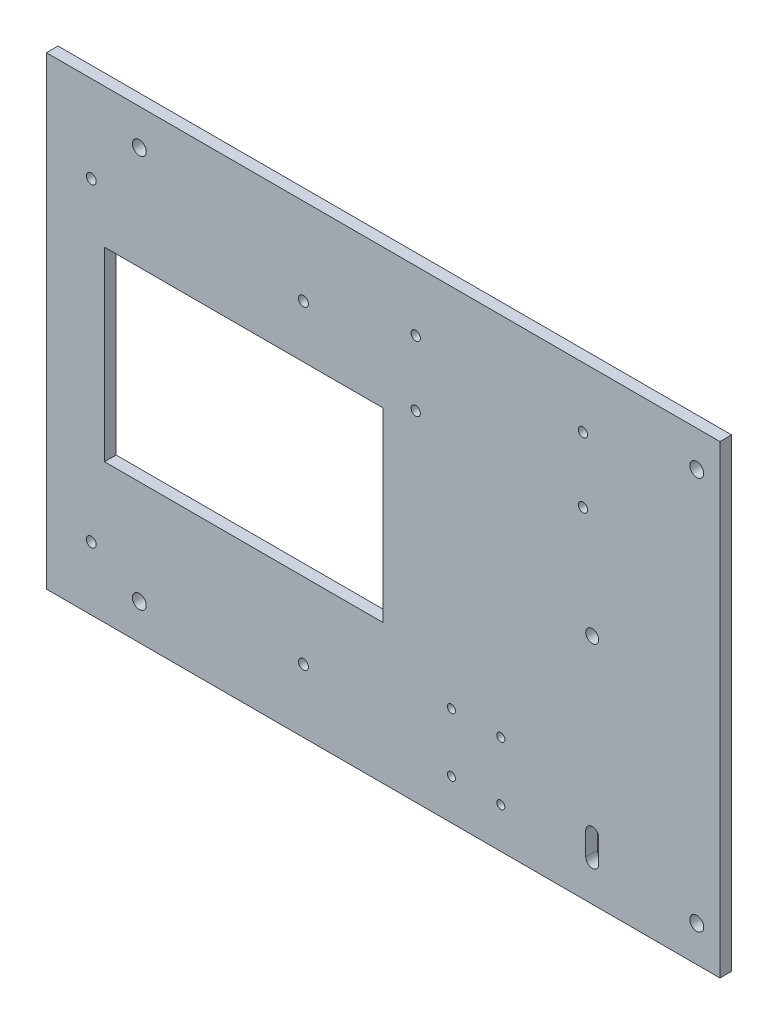
SolidWorks part; units mm, degrees
ref_plane "Front Plane" through (0, 0, 0) normal (0, 0, 1) x (1, 0, 0)
ref_plane "Top Plane" through (0, 0, 0) normal (0, 1, 0) x (1, 0, 0)
ref_plane "Right Plane" through (0, 0, 0) normal (1, 0, 0) x (0, 0, -1)
sketch "Sketch1" plane through (0, 0, 0) normal (0, 0, 1) x (1, 0, 0)
  line L1 (-92.075, 63.5) -> (92.075, 63.5)
  line L2 (-92.075, 63.5) -> (-92.075, -63.5)
  line L3 (-92.075, -63.5) -> (92.075, -63.5)
  line L4 (92.075, 63.5) -> (92.075, -63.5)
  line L5 (-92.075, 63.5) -> (92.075, -63.5) construction
  line L6 (-92.075, -63.5) -> (92.075, 63.5) construction
  point P0 (0, 0)
  dimension "D1" = 184.15
  dimension "D2" = 127
extrude "Boss-Extrude1" add sketch "Sketch1" along normal blind 3.175
sketch "Sketch3" plane through (0, 0, 3.175) normal (0, 0, 1) x (1, 0, 0)
  line L1 (-79.8, 39.825) -> (-21.8, 39.825) construction
  line L2 (-79.8, 39.825) -> (-79.8, -46.175) construction
  line L3 (-79.8, -46.175) -> (-21.8, -46.175) construction
  line L4 (-21.8, 39.825) -> (-21.8, -46.175) construction
  line L5 (-79.8, 39.825) -> (-21.8, -46.175) construction
  line L6 (-79.8, -46.175) -> (-21.8, 39.825) construction
  circle A0 centre (-79.8, 39.825) radius 1.35
  circle A1 centre (-21.8, 39.825) radius 1.35
  circle A2 centre (-79.8, -46.175) radius 1.35
  circle A3 centre (-21.8, -46.175) radius 1.35
  point P0 (-50.8, -3.175)
  dimension "D3" = 2.7
  dimension "D1" = 58
  dimension "D2" = 86
  dimension "D4" = 50.8
  dimension "D5" = 3.175
extrude "Cut-Extrude1" cut sketch "Sketch3" against normal through all
hole_wizard "#6 Clearance Hole1" positions "Sketch5" profile "Sketch6" hole size "#6" standard "ANSI Inch" end condition through all
sketch "Sketch5" plane through (0, 0, 3.175) normal (0, 0, 1) x (1, 0, 0)
  point P0 (-66.675, 53.721)
  point P7 (85.725, 53.721)
  dimension "D1" = 66.675
  dimension "D2" = 53.721
  dimension "D3" = 152.4
sketch "Sketch6" plane through (-66.675, 53.721, 3.175) normal (1, 0, 0) x (0, -1, 0)
  line L0 (0, 0) -> (0, 3.175)
  line L1 (0, 3.175) -> (1.8986, 3.175)
  line L2 (1.8986, 3.175) -> (1.8986, 0)
  line L5 (1.8986, 0) -> (0, 0)
  line L11 (0, -6.35) -> (0, 107.95) construction
  dimension "Thru Hole Dia." = 3.7973
  dimension "Thru Hole Depth" = 3.175
mirror "Mirror3" about plane through (0, 0, 0) normal (0, 1, 0) of "#6 Clearance Hole1"
sketch "Sketch9" plane through (0, 0, 3.175) normal (0, 0, 1) x (1, 0, 0)
  line L1 (18.65, -36.45) -> (32.15, -36.45) construction
  line L2 (18.65, -36.45) -> (18.65, -52.45) construction
  line L3 (18.65, -52.45) -> (32.15, -52.45) construction
  line L4 (32.15, -36.45) -> (32.15, -52.45) construction
  line L5 (18.65, -36.45) -> (32.15, -52.45) construction
  line L6 (18.65, -52.45) -> (32.15, -36.45) construction
  line L8 (16.5, -34.3) -> (34.3, -34.3) construction
  line L9 (16.5, -34.3) -> (16.5, -54.6) construction
  line L10 (16.5, -54.6) -> (34.3, -54.6) construction
  line L11 (34.3, -34.3) -> (34.3, -54.6) construction
  line L12 (16.5, -34.3) -> (34.3, -54.6) construction
  line L13 (16.5, -54.6) -> (34.3, -34.3) construction
  circle A0 centre (18.65, -36.45) radius 1.1
  circle A1 centre (32.15, -36.45) radius 1.1
  circle A2 centre (32.15, -52.45) radius 1.1
  circle A3 centre (18.65, -52.45) radius 1.1
  point P0 (25.4, -44.45)
  point P10 (25.4, -44.45)
  dimension "D3" = 2.2
  dimension "D1" = 13.5
  dimension "D2" = 16
  dimension "D4" = 44.45
  dimension "D5" = 25.4
  dimension "D6" = 17.8
  dimension "D7" = 20.3
extrude "Cut-Extrude2" cut sketch "Sketch9" against normal through all
sketch "Sketch10" plane through (0, 0, 3.175) normal (0, 0, 1) x (1, 0, 0)
  line L1 (8.89, 46.99) -> (54.61, 46.99) construction
  line L2 (8.89, 46.99) -> (8.89, 29.21) construction
  line L3 (8.89, 29.21) -> (54.61, 29.21) construction
  line L4 (54.61, 46.99) -> (54.61, 29.21) construction
  line L5 (8.89, 46.99) -> (54.61, 29.21) construction
  line L6 (8.89, 29.21) -> (54.61, 46.99) construction
  line L7 (6.35, 49.53) -> (57.15, 49.53) construction
  line L8 (6.35, 49.53) -> (6.35, 26.67) construction
  line L9 (6.35, 26.67) -> (57.15, 26.67) construction
  line L10 (57.15, 49.53) -> (57.15, 26.67) construction
  line L11 (6.35, 49.53) -> (57.15, 26.67) construction
  line L12 (6.35, 26.67) -> (57.15, 49.53) construction
  circle A0 centre (54.61, 46.99) radius 1.27
  circle A1 centre (54.61, 29.21) radius 1.27
  circle A2 centre (8.89, 29.21) radius 1.27
  circle A3 centre (8.89, 46.99) radius 1.27
  point P0 (31.75, 38.1)
  point P15 (31.75, 38.1)
  dimension "D3" = 2.54
  dimension "D4" = 31.75
  dimension "D1" = 45.72
  dimension "D2" = 17.78
  dimension "D5" = 38.1
  dimension "D6" = 50.8
  dimension "D7" = 22.86
extrude "Cut-Extrude3" cut sketch "Sketch10" against normal through all
sketch "Sketch11" plane through (0, 0, 3.175) normal (0, 0, 1) x (1, 0, 0)
  line L0 (57.15, -46.863) -> (57.15, -53.213) construction
  line L1 (58.928, -46.863) -> (58.928, -53.213)
  line L2 (55.372, -46.863) -> (55.372, -53.213)
  circle A0 centre (57.15, 0) radius 1.778
  arc A1 (58.928, -46.863) -> (55.372, -46.863) centre (57.15, -46.863) ccw
  arc A2 (55.372, -53.213) -> (58.928, -53.213) centre (57.15, -53.213) ccw
  point P4 (57.15, -50.038)
  dimension "D1" = 3.556
  dimension "D2" = 1.778
  dimension "D3" = 6.35
  dimension "D6" = 57.15
  dimension "D4" = 50.038
  dimension "D5" = 0
extrude "Cut-Extrude4" cut sketch "Sketch11" against normal through all
sketch "Sketch12" plane through (0, 0, 3.175) normal (0, 0, 1) x (1, 0, 0)
  line L1 (-76.2, 25.4) -> (0, 25.4)
  line L2 (-76.2, 25.4) -> (-76.2, -25.4)
  line L3 (-76.2, -25.4) -> (0, -25.4)
  line L4 (0, 25.4) -> (0, -25.4)
  line L5 (-76.2, 25.4) -> (0, -25.4) construction
  line L6 (-76.2, -25.4) -> (0, 25.4) construction
  point P0 (-38.1, 0)
  dimension "D1" = 76.2
  dimension "D2" = 50.8
  dimension "D3" = 38.1
extrude "Cut-Extrude5" cut sketch "Sketch12" against normal through all
